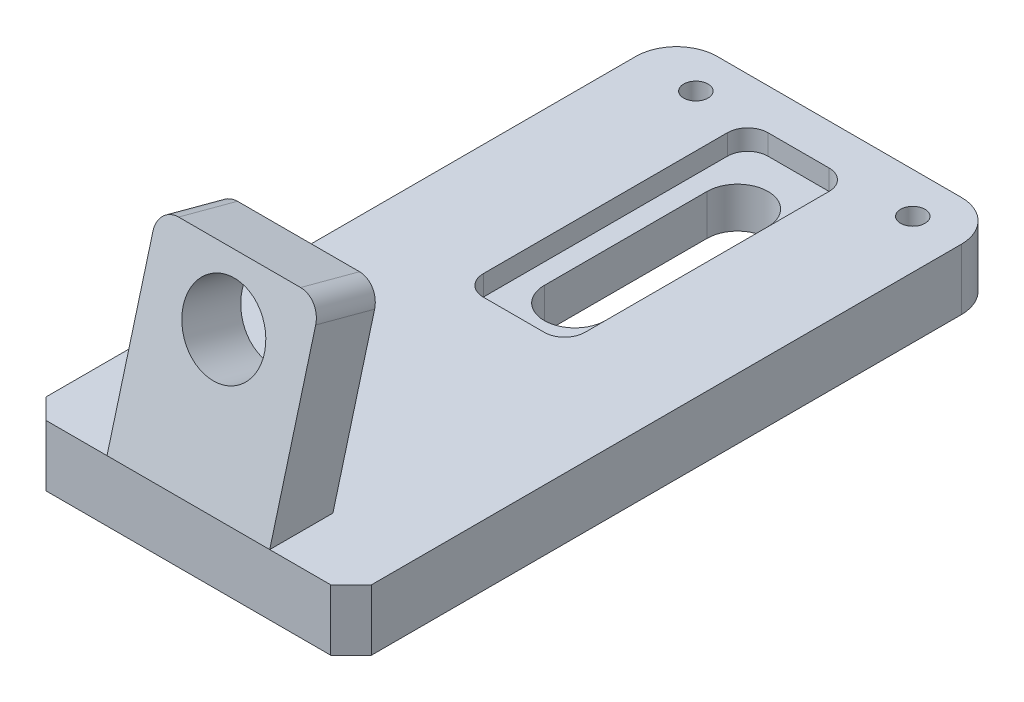
SolidWorks part; units mm, degrees
ref_plane "Front Plane" through (0, 0, 0) normal (0, 0, 1) x (1, 0, 0)
ref_plane "Top Plane" through (0, 0, 0) normal (0, 1, 0) x (1, 0, 0)
ref_plane "Right Plane" through (0, 0, 0) normal (1, 0, 0) x (0, 0, -1)
sketch "Sketch1" plane through (0, 0, 0) normal (0, 1, 0) x (1, 0, 0)
  line L0 (-40, -75) -> (-35, -80)
  line L1 (-35, -80) -> (35, -80)
  line L2 (-40, -75) -> (-40, 70)
  line L3 (-30, 80) -> (30, 80)
  line L4 (40, -75) -> (40, 70)
  line L5 (-40, -80) -> (40, 80) construction
  line L6 (-40, 80) -> (40, -80) construction
  line L7 (35, -80) -> (40, -75)
  line L8 (0, 15) -> (0, 55) construction
  line L9 (-7.5, 15) -> (-7.5, 55)
  line L10 (7.5, 15) -> (7.5, 55)
  arc A0 (30, 80) -> (40, 70) centre (30, 70) cw
  arc A1 (-40, 70) -> (-30, 80) centre (-30, 70) cw
  arc A2 (-7.5, 15) -> (7.5, 15) centre (0, 15) ccw
  arc A3 (7.5, 55) -> (-7.5, 55) centre (0, 55) ccw
  point P0 (0, 0)
  point P18 (0, 35)
  point P23 (0, 0)
  dimension "D6" = 10
  dimension "D7" = 7.5
  dimension "D1" = 80
  dimension "D2" = 160
  dimension "D3" = 5
  dimension "D4" = 45
  dimension "D8" = 40
  dimension "D9" = 25
extrude "Boss-Extrude1" add sketch "Sketch1" along normal blind 15
sketch "Sketch2" plane through (0, 15, 0) normal (0, 1, 0) x (1, 0, 0)
  line L0 (30, 80) -> (-30, 80) construction
  line L1 (-7.5, 70) -> (7.5, 70)
  line L2 (-12.5, 65) -> (-12.5, 5)
  line L3 (-7.5, 0) -> (7.5, 0)
  line L4 (12.5, 65) -> (12.5, 5)
  line L5 (-12.5, 70) -> (12.5, 0) construction
  line L6 (-12.5, 0) -> (12.5, 70) construction
  arc A0 (-7.5, 70) -> (-12.5, 65) centre (-7.5, 65) ccw
  arc A1 (7.5, 70) -> (12.5, 65) centre (7.5, 65) cw
  arc A2 (7.5, 0) -> (12.5, 5) centre (7.5, 5) ccw
  arc A3 (-12.5, 5) -> (-7.5, 0) centre (-7.5, 5) ccw
  point P0 (0, 35)
  point P5 (0, 0)
  dimension "D2" = 5
  dimension "D1" = 70
  dimension "D3" = 25
  dimension "D4" = 10
extrude "Cut-Extrude1" cut sketch "Sketch2" against normal blind 5
sketch "Sketch3" plane through (0, 0, 0) normal (1, 0, 0) x (0, 0, -1)
  line L0 (-80, 15) -> (-67.4064, 62)
  line L1 (-67.4064, 62) -> (-52.9175, 58.1177)
  line L2 (-52.9175, 58.1177) -> (-64.4709, 15)
  line L3 (-64.4709, 15) -> (-80, 15)
  line L4 (-80, 15) -> (-79.5658, 14.9644)
  line L5 (-75, 15) -> (70, 15) construction
  dimension "D1" = 47
  dimension "D2" = 15
  dimension "D3" = 75
extrude "Boss-Extrude2" add sketch "Sketch3" along normal blind 20 and the other way blind 20 separate body contours L3 L2 L1 L0
sketch "Sketch4" plane through (0, 21.0048, 78.391) normal (0, 0.2588, 0.9659) x (1, 0, 0)
  line L0 (-20, 42.4413) -> (20, 42.4413) construction
  circle A0 centre (0, 27.4413) radius 10
  point P2 (0, 42.4413)
  dimension "D1" = 20
  dimension "D2" = 15
extrude "Cut-Extrude2" cut sketch "Sketch4" against normal blind 20
fillet "Fillet1" radius 5 2 edges at (-20, 60.0589, 60.1619) (20, 60.0589, 60.1619)
sketch "Sketch6" plane through (0, 15, 0) normal (0, 1, 0) x (1, 0, 0)
  line L0 (30, 80) -> (-30, 80) construction
  line L2 (12.5, 5) -> (12.5, 65) construction
  point P0 (-25.246, 70)
  point P1 (28.0873, 70)
  dimension "D1" = 10
  dimension "D2" = 10
  dimension "D3" = 53.3333
  dimension "D4" = 15.5873
hole_wizard "M6x1.0 Tapped Hole1" positions "3DSketch1" profile "Sketch7" tap size "M6x1.0" standard "ANSI Metric"
sketch3d "3DSketch1"
  point P0 (-25.246, 15, -70)
  point P3 (28.0873, 15, -70)
sketch "Sketch7" plane through (-25.246, 15, -70) normal (1, 0, 0) x (0, 0, 1)
  line L0 (0, 0) -> (0, 9.5022)
  line L1 (0, 9.5022) -> (2.5, 8)
  line L2 (2.5, 8) -> (2.5, 5)
  line L3 (2.5, 5) -> (3, 5)
  line L4 (3, 5) -> (3, 0)
  line L5 (3, 0) -> (0, 0)
  line L10 (0, 9.5022) -> (-2.5, 8) construction
  line L11 (0, -6.35) -> (0, 107.95) construction
  dimension "Tap Drill Dia." = 5
  dimension "Tap Drill Depth" = 8
  dimension "Thread Major Dia." = 6
  dimension "Thread Depth" = 5
  dimension "Drill Angle" = 118
